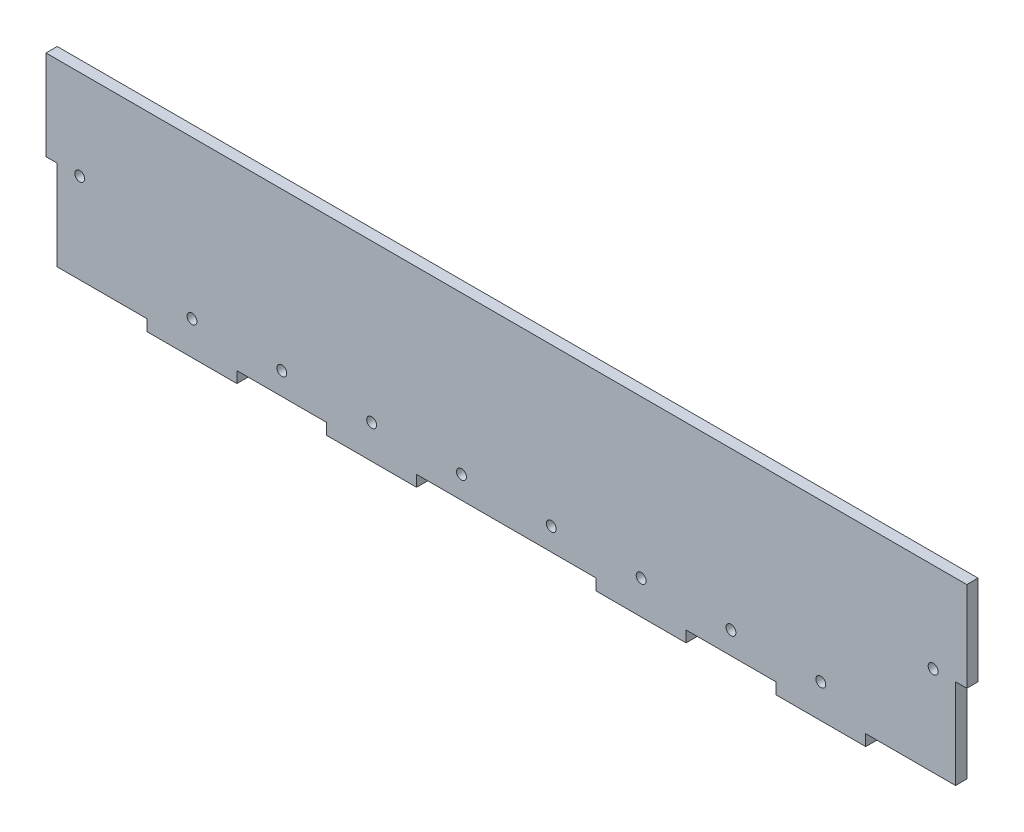
SolidWorks part; units mm, degrees
ref_plane "前视基准面" through (0, 0, 0) normal (0, 0, 1) x (1, 0, 0)
ref_plane "上视基准面" through (0, 0, 0) normal (0, 1, 0) x (1, 0, 0)
ref_plane "右视基准面" through (0, 0, 0) normal (1, 0, 0) x (0, 0, -1)
sketch "草图1" plane through (0, 0, 0) normal (0, 0, 1) x (1, 0, 0)
  line L2 (-200, 150) -> (200, 150)
  line L3 (200, -150) -> (200, -110)
  line L4 (-200, -150) -> (-200, -110)
  line L5 (-200, -150) -> (-160, -150)
  line L6 (-200, -150) -> (-160, -150)
  line L7 (-160, -150) -> (-160, -155)
  line L8 (-160, -155) -> (-120, -155)
  line L9 (-120, -155) -> (-120, -150)
  line L10 (-120, -150) -> (-80, -150)
  line L11 (-80, -150) -> (-80, -155)
  line L12 (-80, -155) -> (-40, -155)
  line L13 (-40, -155) -> (-40, -150)
  line L14 (-40, -150) -> (40, -150)
  line L15 (40, -150) -> (40, -155)
  line L16 (40, -155) -> (80, -155)
  line L17 (80, -155) -> (80, -150)
  line L18 (80, -150) -> (120, -150)
  line L19 (120, -150) -> (120, -155)
  line L20 (120, -155) -> (160, -155)
  line L21 (160, -155) -> (160, -150)
  line L22 (80, -150) -> (120, -150)
  line L23 (-120, -150) -> (-80, -150)
  line L24 (-40, -150) -> (40, -150)
  line L25 (160, -150) -> (200, -150)
  line L26 (-200, 110) -> (-200, 150)
  line L27 (-200, -70) -> (-200, -30)
  line L28 (-205, -30) -> (-205, 30)
  line L29 (-205, 30) -> (-200, 30)
  line L30 (-200, 30) -> (-200, 70)
  line L31 (-200, 70) -> (-205, 70)
  line L32 (-205, 70) -> (-205, 110)
  line L33 (-205, 110) -> (-200, 110)
  line L34 (-205, -30) -> (-200, -30)
  line L35 (-200, -70) -> (-205, -70)
  line L36 (-205, -70) -> (-205, -110)
  line L37 (-205, -110) -> (-200, -110)
  line L38 (-200, 30) -> (-200, 70)
  line L39 (200, 110) -> (200, 150)
  line L40 (205, -70) -> (205, -110)
  line L41 (205, -110) -> (200, -110)
  line L42 (200, -70) -> (205, -70)
  line L43 (205, -30) -> (200, -30)
  line L44 (205, -30) -> (205, 30)
  line L45 (205, 30) -> (200, 30)
  line L46 (200, 70) -> (205, 70)
  line L47 (205, 70) -> (205, 110)
  line L48 (205, 110) -> (200, 110)
  line L49 (200, 30) -> (200, 70)
  line L50 (200, -70) -> (200, -30)
  circle A0 centre (-140, -140) radius 2.2
  circle A1 centre (-100, -140) radius 2.2
  circle A2 centre (-60, -140) radius 2.2
  circle A3 centre (-20, -140) radius 2.2
  circle A4 centre (20, -140) radius 2.2
  circle A5 centre (60, -140) radius 2.2
  circle A6 centre (100, -140) radius 2.2
  circle A7 centre (140, -140) radius 2.2
  circle A8 centre (-190, 110) radius 2.2
  circle A9 centre (-190, 70) radius 2.2
  circle A10 centre (-190, 30) radius 2.2
  circle A11 centre (-190, -30) radius 2.2
  circle A12 centre (-190, -70) radius 2.2
  circle A13 centre (-190, -110) radius 2.2
  circle A14 centre (190, -110) radius 2.2
  circle A15 centre (190, -70) radius 2.2
  circle A16 centre (190, -30) radius 2.2
  circle A17 centre (190, 30) radius 2.2
  circle A18 centre (190, 70) radius 2.2
  circle A19 centre (190, 110) radius 2.2
extrude "凸台-拉伸1" add sketch "草图1" along normal blind 5 contours L42 L50 L43 L44 L45 L49 L46 L47 L48 L39 L2 L26 L33 L32 L31 L30 L29 L28 L34 L27 L35 L36 L37 L4 L5 L7 L8 L9 L10 L11 L12 L13 L14 L15 L16 L17 L18 L19 L20 L21 L25 L3 L41 L40 A18 A16 A14
sketch "草图2" plane through (0, 0, 5) normal (0, 0, 1) x (1, 0, 0)
  line L0 (-205, -70) -> (205, -70)
  line L1 (-205, -70) -> (-205, 156.1054)
  line L2 (205, -70) -> (205, 156.1054)
  line L3 (-205, 156.1054) -> (205, 156.1054)
extrude "切除-拉伸2" cut sketch "草图2" against normal blind 5
sketch "草图4" plane through (0, 0, 5) normal (0, 0, 1) x (1, 0, 0)
  line L0 (-205, -70) -> (205, -70)
  line L1 (-205, -70) -> (-205, -89.4867)
  line L2 (205, -70) -> (205, -89.4867)
  line L3 (-205, -89.4867) -> (205, -89.4867)
extrude "凸台-拉伸3" add sketch "草图4" against normal blind 5
